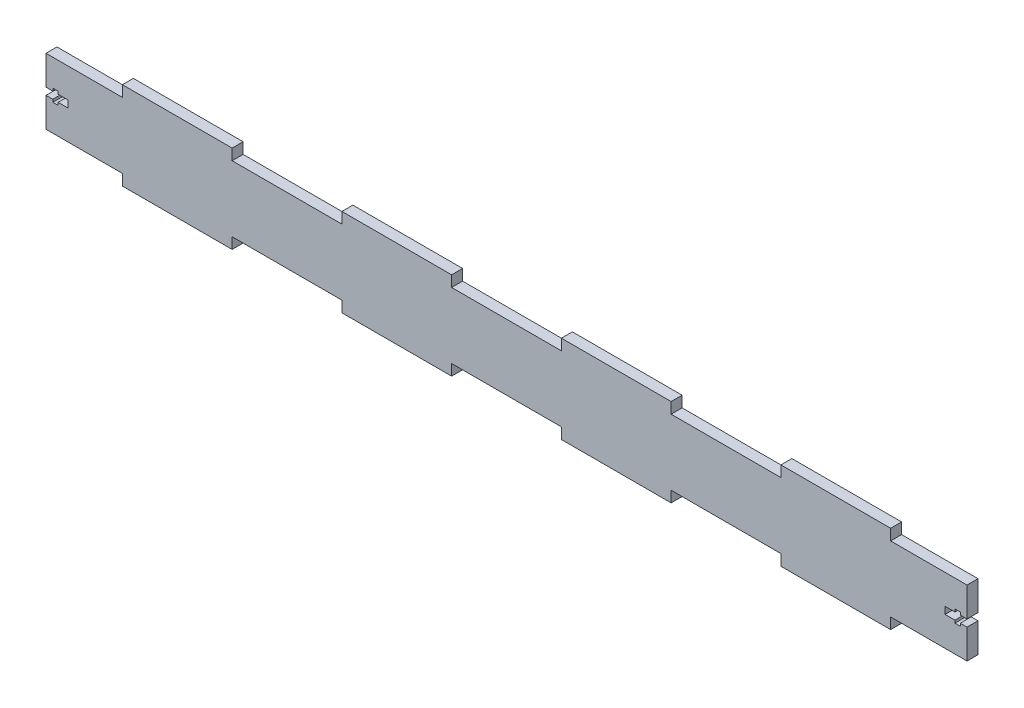
SolidWorks part; units mm, degrees
material "Acrylique (impact moyen-haut)"
ref_plane "Plan de face" through (0, 0, 0) normal (0, 0, 1) x (1, 0, 0)
ref_plane "Plan de dessus" through (0, 0, 0) normal (0, 1, 0) x (1, 0, 0)
ref_plane "Plan de droite" through (0, 0, 0) normal (1, 0, 0) x (0, 0, -1)
sketch "Esquisse1" plane through (0, 0, 0) normal (0, 0, 1) x (1, 0, 0)
  line L0 (-88.8428, 31.8775) -> (-88.8428, 36.8775)
  line L1 (295.9572, 1.8775) -> (261.1572, 1.8775)
  line L2 (295.9572, 1.8775) -> (295.9572, 15.2775)
  line L3 (295.9572, 31.8775) -> (261.1572, 31.8775)
  line L4 (-123.6428, 1.8775) -> (-123.6428, 15.2775)
  line L5 (-88.8428, 36.8775) -> (-38.8428, 36.8775)
  line L6 (-38.8428, 36.8775) -> (-38.8428, 31.8775)
  line L7 (61.1572, 36.8775) -> (61.1572, 31.8775)
  line L8 (11.1572, 36.8775) -> (61.1572, 36.8775)
  line L9 (11.1572, 31.8775) -> (11.1572, 36.8775)
  line L10 (161.1572, 36.8775) -> (161.1572, 31.8775)
  line L11 (111.1572, 36.8775) -> (161.1572, 36.8775)
  line L12 (111.1572, 31.8775) -> (111.1572, 36.8775)
  line L13 (261.1572, 36.8775) -> (261.1572, 31.8775)
  line L14 (211.1572, 36.8775) -> (261.1572, 36.8775)
  line L15 (211.1572, 31.8775) -> (211.1572, 36.8775)
  line L16 (-88.8428, 31.8775) -> (-123.6428, 31.8775)
  line L17 (11.1572, 31.8775) -> (-38.8428, 31.8775)
  line L18 (111.1572, 31.8775) -> (61.1572, 31.8775)
  line L19 (211.1572, 31.8775) -> (161.1572, 31.8775)
  line L20 (295.9572, 16.8775) -> (-123.6428, 16.8775) construction
  line L21 (261.1572, -3.1225) -> (261.1572, 1.8775)
  line L22 (211.1572, -3.1225) -> (261.1572, -3.1225)
  line L23 (211.1572, 1.8775) -> (211.1572, -3.1225)
  line L24 (161.1572, -3.1225) -> (161.1572, 1.8775)
  line L25 (111.1572, -3.1225) -> (161.1572, -3.1225)
  line L26 (111.1572, 1.8775) -> (111.1572, -3.1225)
  line L27 (61.1572, -3.1225) -> (61.1572, 1.8775)
  line L28 (11.1572, -3.1225) -> (61.1572, -3.1225)
  line L29 (11.1572, 1.8775) -> (11.1572, -3.1225)
  line L30 (-38.8428, -3.1225) -> (-38.8428, 1.8775)
  line L31 (-88.8428, -3.1225) -> (-38.8428, -3.1225)
  line L32 (-88.8428, 1.8775) -> (-88.8428, -3.1225)
  line L33 (211.1572, 1.8775) -> (161.1572, 1.8775)
  line L34 (111.1572, 1.8775) -> (61.1572, 1.8775)
  line L35 (11.1572, 1.8775) -> (-38.8428, 1.8775)
  line L36 (-88.8428, 1.8775) -> (-123.6428, 1.8775)
  line L37 (-123.6428, 18.4775) -> (-120.5609, 18.4775)
  line L38 (-113.6428, 18.4775) -> (-113.6428, 15.2775)
  line L39 (-113.6428, 15.2775) -> (-118.1409, 15.2775)
  line L40 (-120.5609, 18.4775) -> (-120.5609, 19.6775)
  line L41 (-120.5609, 19.6775) -> (-118.1409, 19.6775)
  line L42 (-118.1409, 19.6775) -> (-118.1409, 18.4775)
  line L43 (-120.5609, 15.2775) -> (-120.5609, 14.0775)
  line L44 (-120.5609, 14.0775) -> (-118.1409, 14.0775)
  line L45 (-118.1409, 14.0775) -> (-118.1409, 15.2775)
  line L46 (-118.1409, 18.4775) -> (-113.6428, 18.4775)
  line L47 (-120.5609, 15.2775) -> (-123.6428, 15.2775)
  line L48 (-123.6428, 18.4775) -> (-123.6428, 31.8775)
  line L49 (86.1572, 16.8775) -> (86.1572, 31.8775) construction
  line L50 (295.9572, 18.4775) -> (292.8754, 18.4775)
  line L51 (292.8754, 18.4775) -> (292.8754, 19.6775)
  line L52 (292.8754, 19.6775) -> (290.4554, 19.6775)
  line L53 (290.4554, 19.6775) -> (290.4554, 18.4775)
  line L54 (290.4554, 18.4775) -> (285.9572, 18.4775)
  line L55 (285.9572, 18.4775) -> (285.9572, 15.2775)
  line L56 (285.9572, 15.2775) -> (290.4554, 15.2775)
  line L57 (290.4554, 14.0775) -> (290.4554, 15.2775)
  line L58 (292.8754, 14.0775) -> (290.4554, 14.0775)
  line L59 (292.8754, 15.2775) -> (292.8754, 14.0775)
  line L60 (292.8754, 15.2775) -> (295.9572, 15.2775)
  line L61 (295.9572, 18.4775) -> (295.9572, 31.8775)
  point P40 (-113.6428, 16.8775)
  dimension "D1" = 419.6
  dimension "D2" = 30
  dimension "D3" = 5
  dimension "D4" = 34.8
  dimension "D5" = 50
  dimension "D7" = 3.2
  dimension "D8" = 10
  dimension "D9" = 2.42
  dimension "D10" = 2.42
  dimension "D11" = 1.2
  dimension "D12" = 1.2
  dimension "D6" = 4
extrude "Boss.-Extru.1" add sketch "Esquisse1" along normal blind 5
sketch "Esquisse2" plane through (0, 0, 0) normal (0, 0, -1) x (-1, 0, 0)
  line L0 (-295.9572, 10.6717) -> (123.6428, 10.6717) construction
  line L1 (-295.9572, 1.8775) -> (-295.9572, 15.2775) construction
  line L2 (123.6428, 15.2775) -> (123.6428, 1.8775) construction
  text T0 "<b>AEROBOTIX EUROBOT 2022</b>" font "Century Gothic" height in points 48
extrude "Enlèv. mat.-Extru.2" cut sketch "Esquisse2" against normal blind 1
